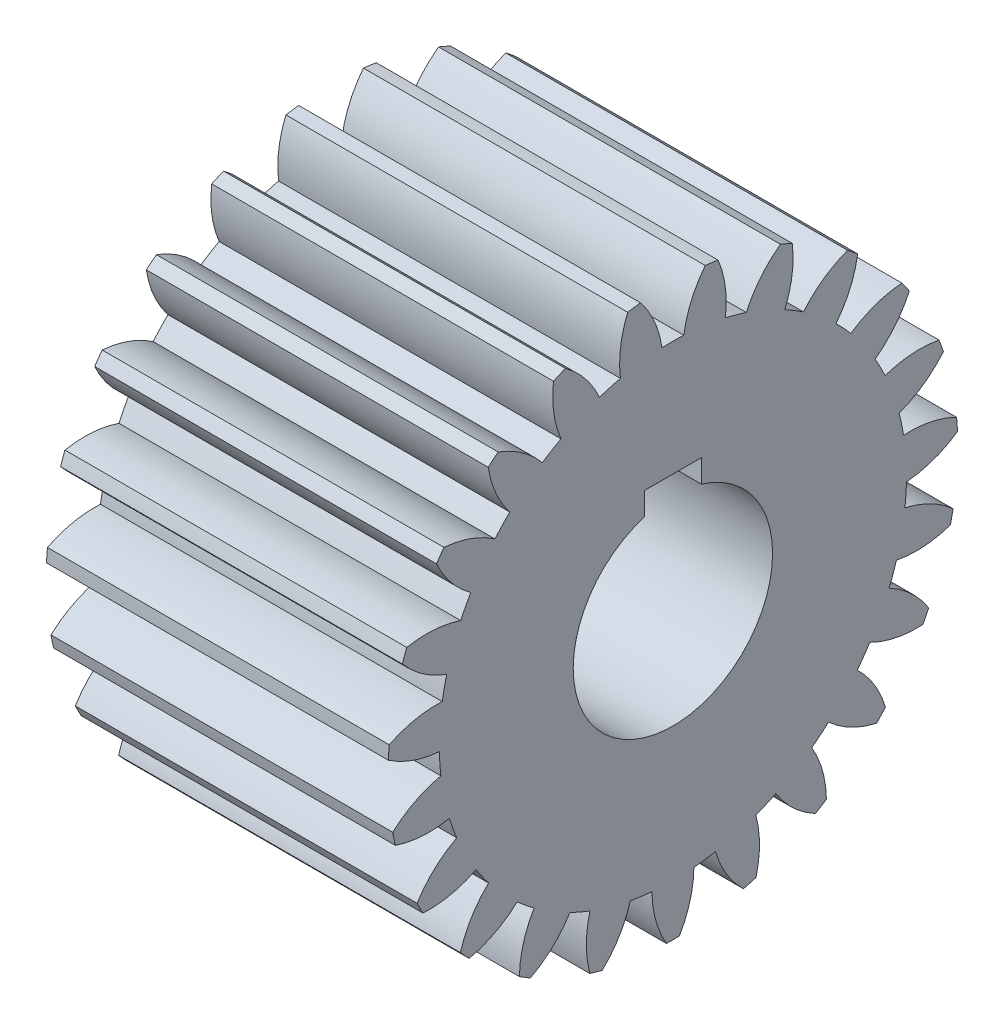
SolidWorks part; units mm, degrees
ref_plane "Plane1" through (0, 0, 0) normal (0, 0, 1) x (1, 0, 0)
ref_plane "Plane2" through (0, 0, 0) normal (0, 1, 0) x (1, 0, 0)
ref_plane "Plane3" through (0, 0, 0) normal (1, 0, 0) x (0, 0, -1)
sketch "HoldingSke" plane through (0, 0, 0) normal (0, 1, 0) x (1, 0, 0)
  line L0 (0, 0) -> (0.2301, -0.0977)
  line L1 (-15, 0) -> (100, 0) construction
  line L2 (0, 0) -> (-2.1039, 2.3779)
  line L3 (0, 0) -> (-11.863, 4.5341)
  line L4 (0, 0) -> (7.9495, 3.3744)
  line L5 (0, 0) -> (-46.8476, -17.4728)
  line L6 (0, 0) -> (-49.7378, -33.5582)
  line L7 (-2.1039, 2.3779) -> (10.8111, 60.9715)
  line L8 (-76.2, 54.61) -> (-72.9, 54.61)
  line L9 (-71.009, 38.7566) -> (-53.1078, 45.2721)
  line L10 (-76.2, 71.12) -> (104.1128, 71.12)
  line L11 (0, 0) -> (-60, 0)
  line L12 (-76.2, 101.6) -> (-76.073, 101.6)
  line L13 (24.9733, 27.94) -> (52.9518, 28.4284)
  line L14 (24.9733, 27.94) -> (24.9743, 27.94)
  line L15 (24.9733, 27.94) -> (100.4006, 29.5858)
  line L16 (-63.627, -4) -> (-12.827, -4)
  circle A0 centre (0, 0) radius 17.5
  circle A1 centre (0, 0) radius 37.5
  circle A2 centre (0, 0) radius 37.5
  circle A3 centre (0, 0) radius 17.5
  dimension "MHD" = 75
  dimension "Hub_dia" = 75
  dimension "Bore" = 35
  dimension "MBD" = 35
  dimension "Num_teeth" = 23
  dimension "Pitch" = 0.25
  dimension "Overall_len" = 50
  dimension "Show_teeth" = 23
  dimension "Thickness" = 60
  dimension "OAL" = 60.0001
  dimension "T_dim" = 3.3
  dimension "Ap" = 20
  dimension "H" = 19.05
  dimension "Pitch_radius" = 180.3128
  dimension "Width" = 60
  dimension "Backlash" = 0.127
  dimension "Addendum_fac" = 1
  dimension "Dedendum_fac" = 1.25
  dimension "Clearance_fac" = 0.25
  dimension "Dedendum_add" = 0.001
  dimension "Module" = 4
sketch "BasProSke" plane through (0, 0, 0) normal (0, 1, 0) x (1, 0, 0)
  line L0 (-10, 0) -> (60, 0) construction
  line L1 (0, 0) -> (0, 50)
  line L2 (0, 0) -> (60, 0)
  line L3 (60, 0) -> (60, 50)
  line L4 (60, 50) -> (0, 50)
  dimension "Thickness" = 60
  dimension "Diameter" = 100
revolve "Base-Revolve" add sketch "BasProSke" angle 360 about L0
sketch "TooCutSke" plane through (0, 0, 0) normal (1, 0, 0) x (0, 0, -1)
  line L1 (0, 0) -> (0, 107) construction
  line L2 (0, 0) -> (-3.3613, 45.877) construction
  line L3 (0, 0) -> (-12.5021, 90.9597) construction
  line L4 (-3.3613, 45.877) -> (-6.2511, 45.4798) construction
  arc A0 (1.9097, 40.9545) -> (-1.9097, 40.9545) centre (0, 0) ccw
  arc A1 (5.6984, 49.6998) -> (-5.6984, 49.6998) centre (0, 0) ccw
  circle A2 centre (0, 0) radius 46 construction
  circle A3 centre (0, 0) radius 43.2259 construction
  arc A4 (-1.9097, 40.9545) -> (-5.6984, 49.6998) centre (-20.1117, 38.2622) ccw
  arc A5 (5.6984, 49.6998) -> (1.9097, 40.9545) centre (20.1117, 38.2622) ccw
  dimension "Root_dia" = 81.998
  dimension "Overcut_dia" = 100.0508
  dimension "Pitch_dia" = 92
  dimension "Base_dia" = 86.4517
  dimension "Flank_rad" = 18.4
  dimension "Half_ang" = 7.826
  dimension "Half_CT" = 2.9169
extrude "ToothCut" cut sketch "TooCutSke" along normal through all
fillet "Breaks" [suppressed] radius 0.08
fillet "RootFillets" [suppressed] radius 1.001
pattern_circular "TeethCuts" count 23 every 15.652 about axis through (-10, 0, 0) along (1, 0, 0) of "ToothCut", "RootFillets", "Breaks"
sketch "HubNeaOneSke" plane through (0, 0, 0) normal (-1, 0, 0) x (0, 0, 1)
  circle A0 centre (0, 0) radius 37.5
  dimension "Diameter" = 75
extrude "HubNearOne" [suppressed] add sketch "HubNeaOneSke" along normal blind 12.7001
sketch "HubNeaBotSke" plane through (0, 0, 0) normal (-1, 0, 0) x (0, 0, 1)
  circle A0 centre (0, 0) radius 37.5
  dimension "Diameter" = 75
extrude "HubNearBoth" [suppressed] add sketch "HubNeaBotSke" along normal blind 6.35
ref_plane "FarPln" through (60, 0, 0) normal (1, 0, 0) x (0, 0, -1)
sketch "HubFarSke" plane through (60, 0, 0) normal (1, 0, 0) x (0, 0, -1)
  circle A0 centre (0, 0) radius 37.5
  dimension "Diameter" = 75
extrude "HubFar" [suppressed] add sketch "HubFarSke" along normal blind 6.35
sketch "BorSke" plane through (0, 0, 0) normal (1, 0, 0) x (0, 0, -1)
  circle A0 centre (0, 0) radius 17.5
  dimension "Diameter" = 35
extrude "Bore" cut sketch "BorSke" along normal mid plane 120.0001
sketch "KeySke" plane through (0, 0, 0) normal (1, 0, 0) x (0, 0, -1)
  line L0 (-5, 0) -> (-5, 20.8)
  line L1 (-5, 20.8) -> (5, 20.8)
  line L2 (5, 20.8) -> (5, 0)
  line L3 (0, 0) -> (0, 34) construction
  line L4 (-5, 0) -> (5, 0)
  dimension "Offset" = 20.8
  dimension "Width" = 10
extrude "Keyway" cut sketch "KeySke" along normal mid plane 120.0001
pattern_circular "Keyway2" [suppressed] count 2 every 90 about axis through (-10, 0, 0) along (1, 0, 0)
equation "' \"Module@HoldingSke\" = 6.35"
equation "' \"Num_teeth@HoldingSke\" = 12"
equation "' \"Ap@HoldingSke\" =  20"
equation "' \"Ap@HoldingSke\" = 20"
equation "' \"Width@HoldingSke\" = 0.5 * 25.4"
equation "' \"Hub_dia@HoldingSke\"= 1 * 25.4"
equation "' \"Hub_dia@HoldingSke\" = 1 * 25.4"
equation "' \"Overall_len@HoldingSke\" = 1.0 * 25.4"
equation "' \"Bore@HoldingSke\" = 0.75 * 25.4"
equation "' \"T_dim@HoldingSke\" = 0.1 * 25.4"
equation "' \"Width@KeySke\" = 0.25 * 25.4"
equation "' \"Show_teeth@HoldingSke\" = 13"
equation "' \"Backlash@HoldingSke\" = 0.009 * 25.4"
equation "' \"Addendum_fac@HoldingSke\" = 1.0"
equation "' \"Dedendum_fac@HoldingSke\" = 1.25"
equation "' \"Dedendum_add@HoldingSke\" = 0.00005 * 25.4"
equation "' \"Clearance_fac@HoldingSke\" = 0.25"
equation "\"Pitch@HoldingSke\" = 1 / \"Module@HoldingSke\""
equation "\"Overcut_dia@TooCutSke\" = (\"Num_teeth@HoldingSke\" + 2 * \"Addendum_fac@HoldingSke\") / \"Pitch@HoldingSke\" + 0.002 * 25.4"
equation "\"Pitch_dia@TooCutSke\" = \"Num_teeth@HoldingSke\" / \"Pitch@HoldingSke\""
equation "\"Base_dia@TooCutSke\" = \"Num_teeth@HoldingSke\" / \"Pitch@HoldingSke\" * cos((\"Ap@HoldingSke\"  * 3.14159265 / 180))"
equation "\"Root_dia@TooCutSke\" = (\"Num_teeth@HoldingSke\" + 2) / \"Pitch@HoldingSke\" - 2 * (\"Addendum_fac@HoldingSke\" + \"Dedendum_fac@HoldingSke\") / \"Pitch@HoldingSke\" - \"Dedendum_add@HoldingSke\" * 2"
equation "\"Half_ang@TooCutSke\" = 180 / \"Num_teeth@HoldingSke\""
equation "\"Half_CT@TooCutSke\" = \"Num_teeth@HoldingSke\" / \"Pitch@HoldingSke\" * sin((3.14159265 / 2 / \"Num_teeth@HoldingSke\")) / 2 - 7 * \"Backlash@HoldingSke\" / 4"
equation "\"Flank_rad@TooCutSke\" = \"Num_teeth@HoldingSke\" / \"Pitch@HoldingSke\" / 5"
equation "\"Radius@RootFillets\" = \"Clearance_fac@HoldingSke\" / \"Pitch@HoldingSke\" + \"Dedendum_add@HoldingSke\""
equation "\"Break_rad@Breaks\" = 0.02 / \"Pitch@HoldingSke\""
equation "\"Thickness@HoldingSke\" = \"Width@HoldingSke\""
equation "\"OAL@HoldingSke\" = \"Thickness@HoldingSke\""
equation "\"MHD@HoldingSke\" = (\"Num_teeth@HoldingSke\" + 2) / \"Pitch@HoldingSke\" - 2 * (\"Addendum_fac@HoldingSke\" + \"Dedendum_fac@HoldingSke\")  / \"Pitch@HoldingSke\" - \"Dedendum_add@HoldingSke\" * 2"
equation "\"MBD@HoldingSke\" = (\"Num_teeth@HoldingSke\" + 2) / \"Pitch@HoldingSke\" - 2 * (\"Addendum_fac@HoldingSke\" + \"Dedendum_fac@HoldingSke\")  / \"Pitch@HoldingSke\" - \"Dedendum_add@HoldingSke\" * 2 - 0.002 * 25.4"
equation "\"MHD@HoldingSke\" = ((sgn( \"MHD@HoldingSke\" - \"Hub_dia@HoldingSke\" )-1)*( \"MHD@HoldingSke\" - \"Hub_dia@HoldingSke\" ))/-2+ \"Hub_dia@HoldingSke\""
equation "\"MBD@HoldingSke\" = ((sgn( \"MBD@HoldingSke\" - \"Bore@HoldingSke\" )-1)*( \"MBD@HoldingSke\" - \"Bore@HoldingSke\" ))/-2+ \"Bore@HoldingSke\""
equation "\"OAL@HoldingSke\" = ((sgn( \"OAL@HoldingSke\" - \"Overall_len@HoldingSke\" )+1)*( \"OAL@HoldingSke\" - \"Overall_len@HoldingSke\" ))/2 + \"Overall_len@HoldingSke\" + 0.000002 * 25.4"
equation "\"Num_teeth@TeethCuts\" = int( \"Show_teeth@HoldingSke\" ) + 1"
equation "\"Num_teeth@TeethCuts\" = ((sgn( \"Num_teeth@TeethCuts\" - \"Num_teeth@HoldingSke\" )-1)*( \"Num_teeth@TeethCuts\" - \"Num_teeth@HoldingSke\" ))/-2+ \"Num_teeth@HoldingSke\""
equation "\"Num_teeth@TeethCuts\" = ((sgn( \"Num_teeth@TeethCuts\" - 2.0)+1)*( \"Num_teeth@TeethCuts\" - 2.0))/2 +2.0"
equation "\"Angle@TeethCuts\" = 360.0 / \"Num_teeth@HoldingSke\""
equation "\"Diameter@BasProSke\" = (\"Num_teeth@HoldingSke\" + 2 * \"Addendum_fac@HoldingSke\") / \"Pitch@HoldingSke\""
equation "\"Thickness@BasProSke\"  = \"Thickness@HoldingSke\""
equation "' \"Fillet_rad@BasProSke\" =  \"Thickness@HoldingSke\" * 0.05"
equation "' \"Fillet_rad@BasProSke\" = \"Thickness@HoldingSke\" * 0.05"
equation "\"MHD@HoldingSke\" = ((sgn( \"MHD@HoldingSke\" - \"Root_dia@TooCutSke\" )-1)*( \"MHD@HoldingSke\" - \"Root_dia@TooCutSke\" ))/-2+ \"Root_dia@TooCutSke\""
equation "\"Diameter@HubNeaOneSke\" = \"MHD@HoldingSke\""
equation "\"Length@HubNearOne\" = \"OAL@HoldingSke\" - \"Thickness@BasProSke\""
equation "\"Diameter@HubNeaBotSke\" = \"MHD@HoldingSke\""
equation "\"Length@HubNearBoth\" = ( \"OAL@HoldingSke\" - \"Thickness@BasProSke\" ) / 2.0"
equation "\"Thickness@FarPln\" = \"Thickness@BasProSke\""
equation "\"Diameter@HubFarSke\" = \"MHD@HoldingSke\""
equation "\"Length@HubFar\" = ( \"OAL@HoldingSke\" - \"Thickness@BasProSke\" ) / 2.0"
equation "\"Diameter@BorSke\" = \"MBD@HoldingSke\""
equation "\"D1@Bore\" = \"OAL@HoldingSke\" * 2.0"
equation "\"D1@Keyway\" = \"OAL@HoldingSke\" * 2.0"
equation "\"Offset@KeySke\" = \"T_dim@HoldingSke\" + \"MBD@HoldingSke\" / 2.0"
